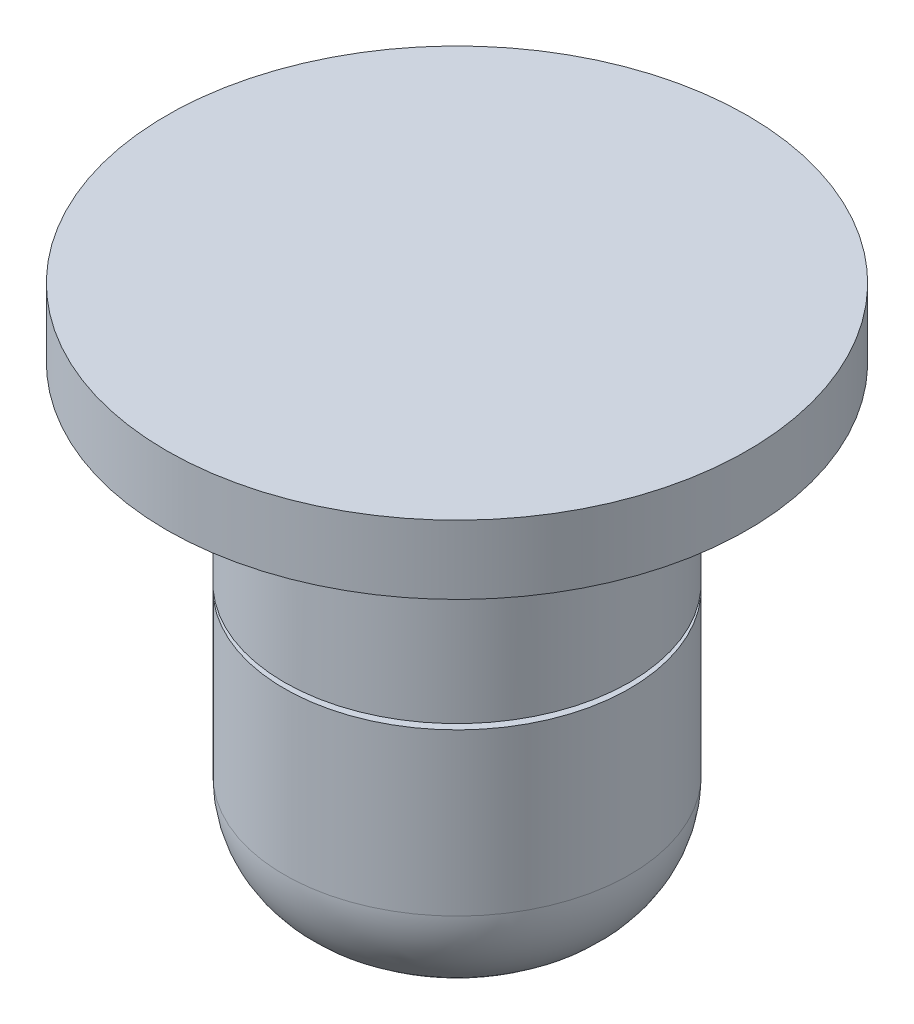
SolidWorks part; units mm, degrees
ref_plane "Front Plane" through (0, 0, 0) normal (0, 0, 1) x (1, 0, 0)
ref_plane "Top Plane" through (0, 0, 0) normal (0, 1, 0) x (1, 0, 0)
ref_plane "Right Plane" through (0, 0, 0) normal (1, 0, 0) x (0, 0, -1)
sketch "Sketch1" plane through (0, 0, 0) normal (0, 0, 1) x (1, 0, 0)
  line L0 (0, 9.7409) -> (10.6796, 9.7409)
  line L1 (10.6796, 9.7409) -> (10.6796, 7.2158)
  line L2 (10.6796, 7.2158) -> (6.35, 7.2158)
  line L3 (6.35, 7.2158) -> (6.35, -5.9309)
  line L4 (2.54, -9.7409) -> (0, -9.7409)
  line L5 (0, -9.7409) -> (0, 9.7409)
  arc A0 (6.35, -5.9309) -> (2.54, -9.7409) centre (2.54, -5.9309) cw
  point P9 (6.35, -9.7409)
  point P10 (0, 0)
  dimension "D2" = 3.81
  dimension "D1" = 6.35
revolve "Revolve1" add sketch "Sketch1" angle 360 about L5
sketch "Sketch2" plane through (0, 0, 0) normal (0, 0, 1) x (1, 0, 0)
  line L1 (-36.4156, 0) -> (36.4156, 0)
  line L2 (-36.4156, 0) -> (-36.4156, 0.2)
  line L3 (-36.4156, 0.2) -> (36.4156, 0.2)
  line L4 (36.4156, 0) -> (36.4156, 0.2)
  dimension "D1" = 0.2
extrude "Cut-Extrude1" cut sketch "Sketch2" against normal through all both and the other way through all
